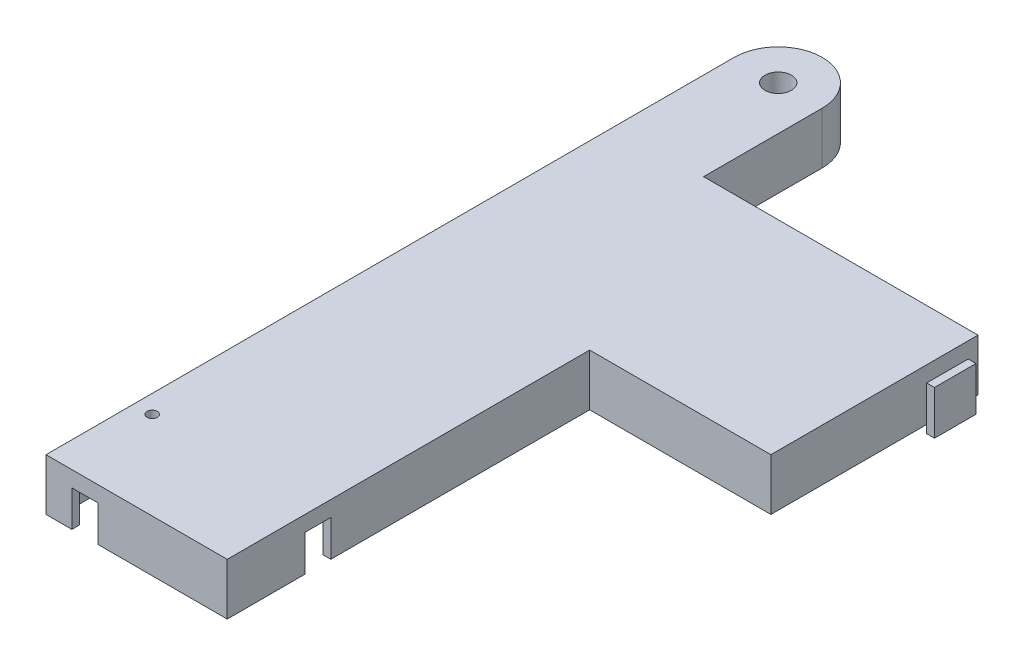
SolidWorks part; units mm, degrees
ref_plane "Front Plane" through (0, 0, 0) normal (0, 0, 1) x (1, 0, 0)
ref_plane "Top Plane" through (0, 0, 0) normal (0, 1, 0) x (1, 0, 0)
ref_plane "Right Plane" through (0, 0, 0) normal (1, 0, 0) x (0, 0, -1)
sketch "CornerrSketch1" plane through (0, 0, 0) normal (0, 1, 0) x (1, 0, 0)
  line L0 (140, 220) -> (140, 140)
  line L2 (0, 0) -> (0, 265.825)
  line L5 (140, 140) -> (70, 140)
  line L6 (70, 140) -> (70, 0)
  line L7 (0, 0) -> (70, 0)
  line L9 (34, 265.825) -> (34, 220)
  line L10 (34, 220) -> (140, 220)
  arc A0 (34, 265.825) -> (0, 265.825) centre (17, 265.825) ccw
  point P2 (17, 282.825)
  point P8 (0, 132.9125)
  dimension "D3" = 34
  dimension "D4" = 80
  dimension "D1" = 220
  dimension "D5" = 45.825
  dimension "D6" = 282.825
  dimension "D7" = 140
  dimension "D11" = 70
extrude "CornerBoss-Extrude1" add sketch "CornerrSketch1" along normal blind 20
shell "Shell2" thickness 3
sketch "PadSketch3" plane through (0, 17, 0) normal (0, -1, 0) x (1, 0, 0)
  line L0 (0, -265.825) -> (0, 0) construction
  line L1 (140, -220) -> (34, -220) construction
  circle A0 centre (17, -265.825) radius 12
  circle A1 centre (7, -34) radius 5
  dimension "D1" = 24
  dimension "D2" = 10
  dimension "D3" = 7
  dimension "D4" = 186
extrude "PadBoss-Extrude2" add sketch "PadSketch3" along normal blind 10
sketch "StepperShaftHoleSketch4" plane through (0, 7, 0) normal (0, -1, 0) x (1, 0, 0)
  circle A0 centre (17, -265.825) radius 5.1
  circle A1 centre (7, -34) radius 2
  dimension "D1" = 10.2
  dimension "D2" = 4
extrude "StepperShaftCut-Extrude2" cut sketch "StepperShaftHoleSketch4" against normal through all
sketch "ThreadedNutMountHolesSketch5" plane through (0, 7, 0) normal (0, -1, 0) x (-1, 0, 0)
  circle A8 centre (-17, 273.825) radius 2
  circle A9 centre (-9, 265.825) radius 2
  circle A10 centre (-17, 257.825) radius 2
  circle A11 centre (-25, 265.825) radius 2
  dimension "D1" = 4
  dimension "D2" = 8
  dimension "D3" = 16
  dimension "D5" = 16
extrude "ThreadedNutMountHolesCut-Extrude4" cut sketch "ThreadedNutMountHolesSketch5" against normal blind 10
sketch "TRPegSketch1" plane through (140, 0, 0) normal (1, 0, 0) x (0, 0, -1)
  line L0 (220, 20) -> (220, 0) construction
  line L1 (200.1, 13.9) -> (209.9, 13.9)
  line L2 (200.1, 13.9) -> (200.1, 0)
  line L3 (200.1, 0) -> (209.9, 0)
  line L4 (209.9, 13.9) -> (209.9, 0)
  line L5 (140, 0) -> (220, 0) construction
  point P6 (220, 10)
  dimension "D1" = 10.1
  dimension "D2" = 13.9
  dimension "D3" = 9.8
extrude "TRPegBoss-Extrude1" add sketch "TRPegSketch1" along normal blind 3.1
sketch "TRPegCapSketch2" plane through (143.1, 0, 0) normal (1, 0, 0) x (0, 0, -1)
  line L0 (200.1, 0) -> (209.9, 0) construction
  line L1 (197.1, 17) -> (213.1, 17)
  line L2 (197.1, 17) -> (197.1, 0)
  line L3 (197.1, 0) -> (213.1, 0)
  line L4 (213.1, 17) -> (213.1, 0)
  line L5 (200.1, 13.9) -> (200.1, 0) construction
  dimension "D1" = 16
  dimension "D2" = 3
  dimension "D3" = 17
extrude "TRPegCapBoss-Extrude2" add sketch "TRPegCapSketch2" along normal blind 3
sketch "BottomPegHoleSketch3" plane through (0, 0, 0) normal (0, 0, 1) x (1, 0, 0)
  line L0 (0, 0) -> (70, 0) construction
  line L1 (10, 13.9) -> (20, 13.9)
  line L2 (10, 13.9) -> (10, 0)
  line L3 (10, 0) -> (20, 0)
  line L4 (20, 13.9) -> (20, 0)
  line L5 (0, 20) -> (0, 0) construction
  line L6 (143.1, 13.9) -> (140, 13.9) construction
  dimension "D2" = 10
  dimension "D3" = 10
extrude "BottomPegHoleCut-Extrude1" cut sketch "BottomPegHoleSketch3" against normal blind 3
sketch "BedCenterPegHoleCutSketch1" plane through (70, 0, 0) normal (1, 0, 0) x (0, 0, -1)
  line L0 (0, 0) -> (140, 0) construction
  line L1 (30, 14) -> (40, 14)
  line L2 (30, 14) -> (30, 0)
  line L3 (30, 0) -> (40, 0)
  line L4 (40, 14) -> (40, 0)
  line L5 (140, 20) -> (140, 0) construction
  dimension "D2" = 10
  dimension "D1" = 14
  dimension "D3" = 100
extrude "BedCenterPegHoleCut-Extrude1" cut sketch "BedCenterPegHoleCutSketch1" against normal blind 3
equation "\"RailThickness\"= .125in'Spec"
equation "\"StepperMountingHoleDistance\"= 31mm'Spec"
equation "\"StepperMountingHoleOffsetFromLeftOrRightSide\"= \"StepperMountingHoleOffsetFromItsSide\" + \"RailThickness\""
equation "\"StepperMountingHoleOffsetFromItsSide\"= 5.5mm'Spec"
equation "\"FrontBackRailLength\"= 510mm"
equation "\"DistanceBetweenLeftToRightStepperHoles\"= \"FrontBackRailLength\" - \"StepperMountingHoleOffsetFromLeftOrRightSide\" * 2 - \"StepperMountingHoleDistance\"'Equals 461.65"
equation "\"BedThickness\"= 20mm"
equation "\"BedLLongSide\"= \"BedThirdSize\" * 3'Equals 210"
equation "\"BedLShortSide\"= \"BedThirdSize\" * 2'Equals 140"
equation "\"BedLWidth\"= \"BedThirdSize\"'Equals 70"
equation "\"D4@CornerrSketch1\"=\"BedLWidth\" + \"BedIncreasedByWidth\"/2"
equation "\"D1@CornerrSketch1\" = \"BedLLongSide\" + \"BedIncreasedByWidth\" / 2"
equation "\"BedInnerSquareWidth\"= \"BedThirdSize\" * 3'Equals 210"
equation "\"BedWidth\"= \"BedInnerSquareWidth\" + \"BedLWidth\" * 2 + \"BedIncreasedByWidth\"'Equals 370"
equation "\"BedIncreasedByWidth\"= 20mm"
equation "\"BedIncreasedByLength\"= 0mm"
equation "\"BedThirdSize\"= 70mm"
equation "\"D1@TRPegCapSketch2\"=\"BedPegCapWidth\""
equation "\"StandardWallThickness\"= 3mm"
equation "\"D2@TRPegCapSketch2\" = \"StandardWallThickness\""
equation "\"D3@TRPegCapSketch2\"=\"BedPegCapHeight\""
equation "\"D1@TRPegCapBoss-Extrude2\" = \"StandardWallThickness\""
equation "\"D1@BottomPegHoleCut-Extrude1\"=\"StandardWallThickness\""
equation "\"D1@Shell2\"=\"StandardWallThickness\""
equation "\"D2@TRPegSketch1\"=\"BedPegHeight\""
equation "\"D5@CornerrSketch1\"=\"DistanceFromBedSideToStepperHole\""
equation "\"DistanceFromBedFrontToStepperHole\"= \"LeadScrewNutPadSize\" + 10mm"
equation "\"DistanceFromBedSideToStepperHole\"= ( \"DistanceBetweenLeftToRightStepperHoles\" - \"BedWidth\" ) / 2'Equals 45.825"
equation "\"D7@CornerrSketch1\"= \"BedLShortSide\" + \"BedIncreasedByLength\" / 2"
equation "\"D3@CornerrSketch1\"=\"DistanceFromBedFrontToStepperHole\""
equation "\"BedToBuildPlateStandoffPadSize\"= 10mm"
equation "\"LeadScrewNutPadSize\"= \"LeadScrewNutMountingHoleFlangeDiameter\" + 2mm'Equals 24"
equation "\"D1@PadSketch3\" = \"LeadScrewNutPadSize\""
equation "\"D1@StepperShaftHoleSketch4\"=\"LeadScrewNutInnerShaftFlangeDiameter\""
equation "\"D11@CornerrSketch1\"=\"BedLWidth\""
equation "\"LeadScrewNutInnerShaftFlangeDiameter\"= 10.2mm'Spec"
equation "\"LeadScrewNutMountHoleDiameter\"= \"M3HeatInsertHoleDiameter\""
equation "\"LeadScrewNutMountingHoleFlangeDiameter\"= 22mm'Spec"
equation "\"LeadScrewNutMountingHoleDistance\"= 16mm'Spec"
equation "\"D2@ThreadedNutMountHolesSketch5\"=\"LeadScrewNutMountingHoleDistance\" / 2"
equation "\"D3@ThreadedNutMountHolesSketch5\"=\"LeadScrewNutMountingHoleDistance\""
equation "\"D5@ThreadedNutMountHolesSketch5\"=\"LeadScrewNutMountingHoleDistance\""
equation "\"D4@ThreadedNutMountHolesSketch5\"=\"LeadScrewNutMountingHoleDistance\"/2"
equation "\"D1@ThreadedNutMountHolesSketch5\"=\"LeadScrewNutMountHoleDiameter\""
equation "\"LeadScrewNutPadDepth\"= \"BedThickness\" / 2'Equals 10"
equation "\"D1@ThreadedNutMountHolesCut-Extrude4\"=\"LeadScrewNutPadDepth\""
equation "\"D2@PadSketch3\"=\"BedToBuildPlateStandoffPadSize\""
equation "\"D3@PadSketch3\"=\"BedToBuildPlateStandoffHolesDistanceFromFront\""
equation "\"BuildPlateWidth\" = 352mm'Spec"
equation "\"D4@PadSketch3\"=\"BedIncreasedByWidth\"/2 + \"BuildPlateWidth\"/2"
equation "\"D2@StepperShaftHoleSketch4\"=\"M3HeatInsertHoleDiameter\""
equation "\"BuildPlateStandoffHolesDistanceFromFront\"= 7mm"
equation "\"BedToBuildPlateStandoffHolesDistanceFromFront\"= \"BuildPlateStandoffHolesDistanceFromFront\" + \"BedIncreasedByLength\" / 2'Equals 7"
equation "\"BedPegHoleWidth\"= 10mm"
equation "\"BedPegHoleHeight\"= \"BedThickness\" - \"StandardWallThickness\" * 2'Equals 14"
equation "\"BedPegWidth\"= \"BedPegHoleWidth\" - .1mm * 2'For easier assembly"
equation "\"BedPegHeight\"= \"BedPegHoleHeight\" - .1mm'For easier assembly"
equation "\"BedTopPegOffsetFromSide\"= 10mm"
equation "\"BedPegBoss\"= \"StandardWallThickness\" + .1mm'For easier assembly"
equation "\"BedPegCapHeight\"= \"BedThickness\" - \"StandardWallThickness\"'Equals 17"
equation "\"BedPegCapWidth\"= \"BedThickness\" / 2 + \"StandardWallThickness\" * 2'Equals 16"
equation "\"D1@TRPegSketch1\"=\"BedTopPegOffsetFromSide\" + .1mm"
equation "\"D3@TRPegSketch1\"= \"BedPegWidth\""
equation "\"D1@TRPegBoss-Extrude1\"=\"BedPegBoss\""
equation "\"D3@BottomPegHoleSketch3\"=\"BedTopPegOffsetFromSide\""
equation "\"D2@BottomPegHoleSketch3\"=\"BedPegHoleWidth\""
equation "\"D1@BedCenterPegHoleCutSketch1\" = \"BedPegHoleHeight\""
equation "\"D2@BedCenterPegHoleCutSketch1\" = \"BedPegHoleWidth\""
equation "\"D3@BedCenterPegHoleCutSketch1\" = \"BedInnerSquareWidth\" / 2 - \"BedPegHoleWidth\" / 2"
equation "\"D1@BedCenterPegHoleCut-Extrude1\"=\"StandardWallThickness\""
equation "\"M3HeatInsertHoleDiameter\"= 4mm'Spec"
